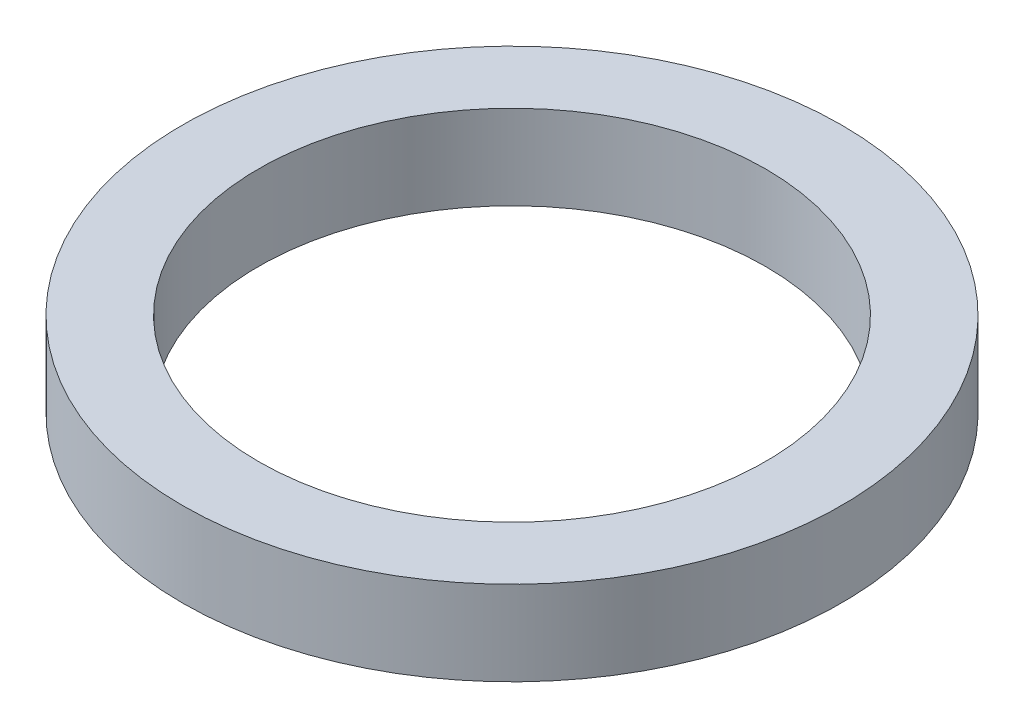
SolidWorks part; units mm, degrees
ref_plane "Front Plane" through (0, 0, 0) normal (0, 0, 1) x (1, 0, 0)
ref_plane "Top Plane" through (0, 0, 0) normal (0, 1, 0) x (1, 0, 0)
ref_plane "Right Plane" through (0, 0, 0) normal (1, 0, 0) x (0, 0, -1)
sketch "Sketch1" plane through (0, 0, 0) normal (0, 1, 0) x (1, 0, 0)
  circle A0 centre (0, 0) radius 30
  circle A1 centre (0, 0) radius 39
  dimension "D1" = 60
  dimension "D2" = 78
extrude "Boss-Extrude1" add sketch "Sketch1" along normal mid plane 10
equation "\"module\" = 0.5"
equation "\"pressure_angle\" = 20.0"
equation "\"h_a\" = 0.5"
equation "\"h_f\" = 0.625"
equation "\"clr_tip_root\" = 0.125"
equation "\"bearing_ID\" = 60"
equation "\"bearing_OD\" = 78"
equation "\"bearing_height\" = 10"
equation "\"clearance_planet\" = 1.5"
equation "\"case_dist\" = 6.5"
equation "\"Motor_case_OD_max\" = 96.5"
equation "\"case_mounting_PCD\" = 89.0"
equation "\"bearing mount thickness\" = 8"
equation "\"case_mounting_hole_dia\" = 3"
equation "\"output_mounting_PCD\" = 86"
equation "\"output_mounting_hole_dia\" = 4"
equation "\"clearance_case_mount_holes_shell_thickness\" = 1"
equation "\"motor_case_OD_base\" = 87.0"
equation "\"sec_carrier_thickness\" = 5"
equation "\"sun_coupler_hub_thickness\" = 4"
equation "\"clearance_sun_coupler_sec_carrier\" = 1.5"
equation "\"clearance_motor_and_case\" = 5.0"
equation "\"motor_OD\" = 72"
equation "\"Motor_case_thickness\" = 2.5"
equation "\"Motor_case_ID\" = 82.0"
equation "\"case_mounting_hole_shift\" = 1.0"
equation "\"output_mounting_nut_wrench_size\" = 7"
equation "\"output_mounting_nut_thickness\" = 3.2"
equation "\"case_mounting_hole_allen_socket_dia\" = 5.5"
equation "\"output_mounting_nut_depth\" = 3"
equation "\"case_mounting_bolt_depth\" = 4.5"
equation "\"Ns\" = 66"
equation "\"ring_radial_thickness\" = 5"
equation "\"ring_to_chamfer_clearance\" = 1.5"
equation "\"Motor_case_OD_base_to_chamfer\" = 5"
equation "\"pattern_offset_from_motor_case_OD_base\" = 3"
equation "\"pattern_bulge_dia\" = 3"
equation "\"pattern_num_bulge\" = 18"
equation "\"pattern_depth\" = 2"
equation "\"motor_height\" = 27"
equation "\"case_mounting_wrench_size\" = 5.5"
equation "\"case_mounting_nut_clearance\" = 2"
equation "\"base_plate_thickness\" = 4"
equation "\"case_mounting_nut_thickness\" = 2.4"
equation "\"case_mounting_surface_height\" = 4"
equation "\"motor_mount_hole_PCD\" = 32"
equation "\"motor_mount_hole_dia\" = 4"
equation "\"motor_mount_hole_num\" = 4"
equation "\"central_hole_offset_from_motor_mount_PCD\" = 5"
equation "\"wire_slot_dist_from_center\" = 26"
equation "\"wire_slot_length\" = 10"
equation "\"wire_slot_radius\" = 2.5"
equation "\"driver_upper_holes_dist_from_center\" = 29"
equation "\"driver_lower_holes_dist_from_center\" = 13"
equation "\"driver_side_holes_dist_from_center\" = 22.5"
equation "\"driver_mount_holes_dia\" = 3"
equation "\"driver_mount_inserts_OD\" = 4.8"
equation "\"driver_mount_thickness\" = 1.5"
equation "\"driver_mount_height\" = 6"
equation "\"air_flow_hole_offset\" = 3"
equation "\"num_planet\" = 6"
equation "\"planet_pin_bolt_dia\" = 5"
equation "\"planet_pin_socket_head_dia\" = 8.5"
equation "\"carrier_PCD\" = 52.5"
equation "\"planet_shaft_dia\" = 8"
equation "\"planet_shaft_step_offset\" = 1"
equation "\"carrier_trapezoidal_support_sun_offset\" = 5"
equation "\"carrier_trapezoidal_support_hole_PCD_offset_bearing_ID\" = 4"
equation "\"carrier_trapezoidal_support_hole_dia\" = 3"
equation "\"carrier_trapezoidal_support_hole_socket_head_dia\" = 5.5"
equation "\"carrier_bearing_step_width\" = 1.5"
equation "\"standard_clearance_1_5mm\" = 1.5"
equation "\"standard_fillet_1_5mm\" = 1.5"
equation "\"sun_shaft_bearing_OD\" = 16"
equation "\"sun_shaft_bearing_width\" = 5"
equation "\"standard_bearing_insertion_chamfer\" = 0.5"
equation "\"D1@Sketch1\"=\"bearing_ID\""
equation "\"D2@Sketch1\"=\"bearing_OD\""
equation "\"D1@Boss-Extrude1\"=\"bearing_height\""
equation "\"carrier_trapezoidal_support_hole_wrench_size\" = 5.5"
equation "\"planet_pin_bolt_wrench_size\" = 8"
equation "\"Np_b\" = 39"
equation "\"pressure angle\" = 20.0"
equation "\"h_b\" = 0.625"
equation "\"dp_s\" = 33.0"
equation "\"db_s\" = 31.00985648593498"
equation "\"fw_s_calc\" = 1.5726146484026726"
equation "\"alpha_s\" = 0.8539582918412449"
equation "\"beta_s\" = 1.0193561435902372"
equation "\"dp_p_b\" = 19.5"
equation "\"db_p_b\" = 18.324006105325214"
equation "\"fw_p_s\" = 22.55792585723615"
equation "\"alpha_p_b\" = 0.8539582918412414"
equation "\"beta_p_b\" = 2.907468031702132"
equation "\"planet_bearing_OD\" = 12"
equation "\"planet_bearing_width\" = 3.5"
equation "\"planet_bore\" = 10"
equation "\"motor_output_hole_PCD\" = 22"
equation "\"motor_output_hole_dia\" = 3"
equation "\"motor_output_hole_num\" = 4"
equation "\"sun_shaft_bearing_ID\" = 8"
equation "\"sun_hub_dia\" = 28.0"
equation "\"sun_central_bolt_dia\" = 5"
equation "\"sun_central_bolt_socket_head_dia\" = 8.5"
equation "\"fw_s_used\" = 48.660536742005725"
equation "\"motor_output_hole_CSK_OD\" = 6"
equation "\"motor_output_hole_CSK_head_height\" = 1.5"
equation "\"bearing_retainer_thickness\" = 2"
equation "\"Np_s\" = 33"
equation "\"fw_p_b\" = 18.602610884769575"
equation "\"dp_p_s\" = 16.5"
equation "\"db_p_s\" = 15.50492824296749"
equation "\"alpha_p_s\" = 0.8539582918412449"
equation "\"beta_p_s\" = 3.7466288708629643"
equation "\"Nr_b\" = 144"
equation "\"dp_r_b\" = 72.0"
equation "\"db_r_b\" = 67.65786869658541"
equation "\"fw_r_b\" = 18.602610884769575"
equation "\"alpha_r_b\" = 0.8539582918412343"
equation "\"beta_r_b\" = 2.9579165836824686"
equation "\"ring_OD_b\" = 82.0"
equation "\"Fillet10\"= IIF ( \"ring_OD_b\" > ( \"bearing_OD\" + 2 * \"bearing mount thickness\" ) , \"suppressed\" , \"unsuppressed\" )"
equation "\"Fillet11\"= IIF ( \"ring_OD_b\" < ( \"bearing_OD\" + 2 * \"bearing mount thickness\" ) , \"suppressed\" , \"unsuppressed\" )"
equation "\"Nr_s\" = 138"
equation "\"clr_tip_root_s\" = 0.125"
equation "\"dp_r_s\" = 69.0"
equation "\"db_r_s\" = 64.83879083422768"
equation "\"fw_r_s\" = 21.05792585723615"
equation "\"alpha_r_s\" = 0.8539582918412485"
equation "\"beta_r_s\" = 3.0122644097694535"
equation "\"small_ring_case_thickness\" = 4"
equation "\"carrier_thickness\" = 4"
equation "\"small_ring_output_wall_thickness\" = 5"
equation "\"small_ring_output_wall_to_bearing_shaft_attachement_hole_dia\" = 4"
equation "\"small_ring_output_wall_to_bearing_shaft_attachement_hole_depth\" = 6.5"
equation "\"small_ring_output_wall_to_bearing_shaft_attachement_nut_wrench\" = 7"
equation "\"small_ring_output_wall_to_bearing_shaft_attachement_nut_thickness\" = 3.2"
equation "\"small_ring_output_wall_to_bearing_shaft_attachement_hole_pcd\" = 12"
equation "\"small_ring_output_wall_to_bearing_shaft_attachement_hole_num\" = 3"
equation "\"small_ring_output_wall_to_bearing_shaft_attachement_hole_CSK_OD\" = 8"
equation "\"small_ring_output_wall_to_bearing_shaft_attachement_hole_CSK_head_height\" = 2.0"
equation "\"carrier_small_ring_inner_bearing_ID\" = 20"
equation "\"carrier_small_ring_inner_bearing_OD\" = 32"
equation "\"carrier_small_ring_inner_bearing_height\" = 7"
equation "\"carrier_small_ring_inner_bearing_flap\" = 2"
equation "\"gear_casing_big_ring_to_bearing_dist\" = 31.55792585723615"
equation "\"gear_casing_thickness\" = 4"
